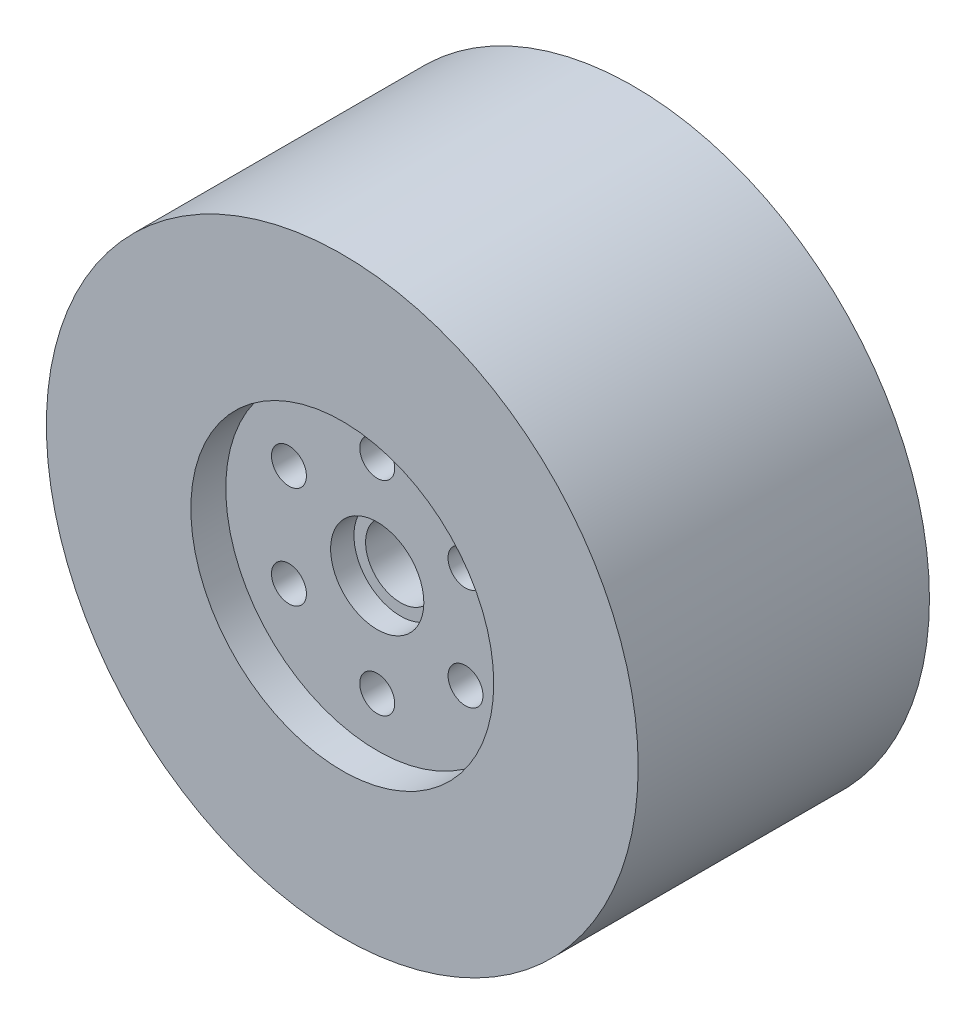
SolidWorks part; units mm, degrees
material "POLYURETHANE (11671)"
ref_plane "Front Plane" through (0, 0, 0) normal (0, 0, 1) x (1, 0, 0)
ref_plane "Top Plane" through (0, 0, 0) normal (0, 1, 0) x (1, 0, 0)
ref_plane "Right Plane" through (0, 0, 0) normal (1, 0, 0) x (0, 0, -1)
sketch "Sketch1" plane through (0, 0, 0) normal (0, 0, 1) x (1, 0, 0)
  circle A0 centre (0, 0) radius 25.4
  dimension "D1" = 50.8
extrude "Boss-Extrude1" add sketch "Sketch1" along normal blind 25
sketch "Sketch2" plane through (0, 0, 25) normal (0, 0, 1) x (1, 0, 0)
  circle A0 centre (0, 0) radius 3
  dimension "D1" = 6
extrude "Cut-Extrude1" cut sketch "Sketch2" against normal through all contours A0
sketch "Sketch4" plane through (0, 0, 0) normal (0, 0, -1) x (-1, 0, 0)
  circle A0 centre (0, 0) radius 4
  dimension "D1" = 8
extrude "Cut-Extrude4" cut sketch "Sketch4" against normal blind 2
sketch "Sketch6" plane through (0, 0, 25) normal (0, 0, 1) x (1, 0, 0)
  circle A0 centre (0, 0) radius 13
  dimension "D1" = 26
extrude "Cut-Extrude6" cut sketch "Sketch6" against normal blind 3
sketch "Sketch9" plane through (0, 0, 22) normal (0, 0, 1) x (1, 0, 0)
  circle A0 centre (0, 8.75) radius 1.5
  dimension "D1" = 3
  dimension "D2" = 8.75
extrude "Cut-Extrude7" cut sketch "Sketch9" against normal blind 5
sketch "Sketch3" plane through (0, 0, 25) normal (0, 0, 1) x (1, 0, 0)
  circle A0 centre (0, 0) radius 4
  dimension "D1" = 8
extrude "Cut-Extrude8" cut sketch "Sketch3" against normal blind 5 contours A0
pattern_circular "CirPattern1" count 6 over 360 about axis through (0, 0, 0) along (0, 0, 1) of "Cut-Extrude7"
